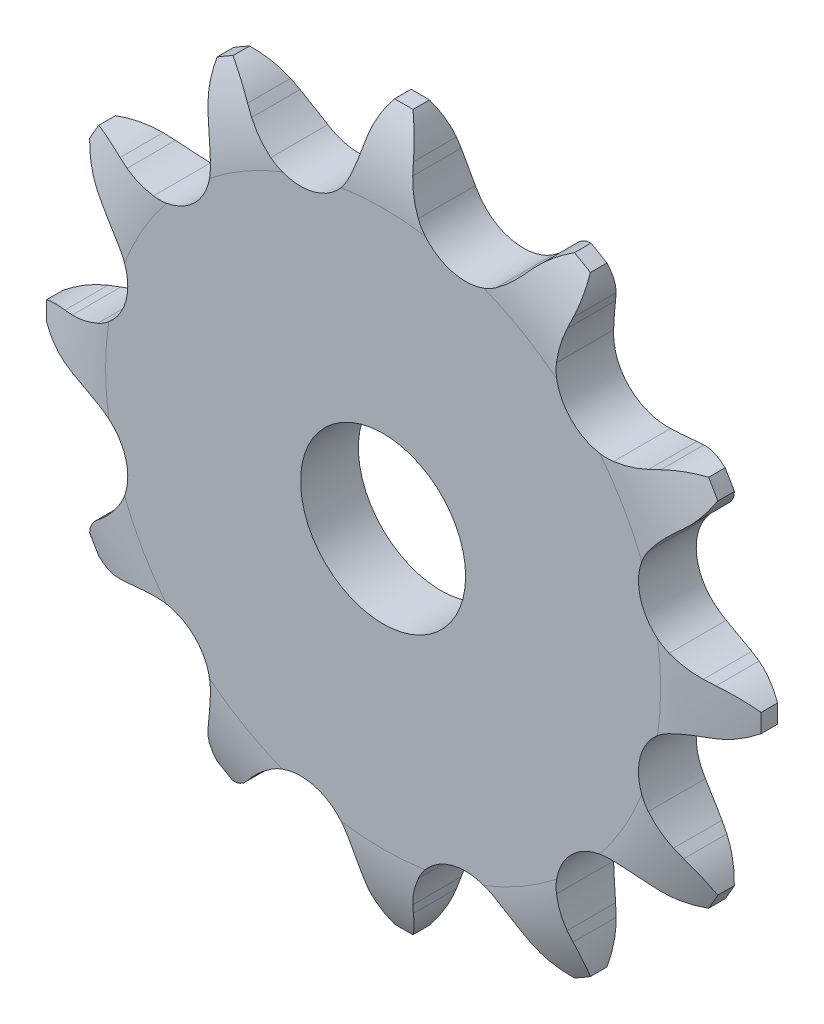
SolidWorks part; units mm, degrees
ref_plane "Front Plane" through (0, 0, 0) normal (0, 0, 1) x (1, 0, 0)
ref_plane "Top Plane" through (0, 0, 0) normal (0, 1, 0) x (1, 0, 0)
ref_plane "Right Plane" through (0, 0, 0) normal (1, 0, 0) x (0, 0, -1)
sketch "Sketch0" plane through (0, 0, 0) normal (0, 0, 1) x (1, 0, 0)
  line L0 (4, -14.9282) -> (0, 0) construction
  line L1 (0, 0) -> (10.9282, -10.9282) construction
  line L2 (0, 0) -> (-4, -14.9282) construction
  line L3 (4, -14.9282) -> (10.9282, -10.9282) construction
  line L4 (4, -14.9282) -> (-4, -14.9282) construction
  line L5 (6.9269, -14.2183) -> (6.5992, -13.85)
  line L6 (4, -14.9282) -> (0, -16) construction
  line L7 (1.1103, -15.7769) -> (1.21, -15.294)
  line L8 (0, -14.9282) -> (0, -17.3282) construction
  line L9 (5.463, -12.8389) -> (1.7057, -18.2048) construction
  line L10 (0, 0) -> (0, -14.9282) construction
  line L11 (6.5992, -13.85) -> (1.7057, -18.2048) construction
  line L12 (0, -17.3282) -> (0, -17.8633) construction
  line L13 (10.0622, -11.4282) -> (6.9269, -14.2183) construction
  circle A0 centre (0, 0) radius 17.3282 construction
  circle A1 centre (0, 0) radius 15.4548 construction
  arc A2 (-3.8269, -19.0429) -> (12.8356, -14.5782) centre (0, 0) ccw
  circle A3 centre (0, 0) radius 17.8633 construction
  circle A4 centre (4, -14.9282) radius 2.5 construction
  arc A7 (5.463, -12.8389) -> (1.6884, -13.8503) centre (4, -14.9282) ccw
  circle A8 centre (4, -14.9282) radius 2.5506 construction
  arc A9 (6.9269, -14.2183) -> (12.8356, -14.5782) centre (10.0622, -11.4282) ccw
  arc A10 (6.5992, -13.85) -> (5.463, -12.8389) centre (1.7057, -18.2048) ccw
  arc A11 (1.1103, -15.7769) -> (-3.8269, -19.0429) centre (-3, -14.9282) cw
  arc A12 (1.21, -15.294) -> (1.6884, -13.8503) centre (7.6252, -16.6187) cw
  dimension "D1" = 2.5506
  dimension "R" = 2.5506
sketch "Sketch1" plane through (0, 0, 0) normal (1, 0, 0) x (0, 0, -1)
  line L0 (1.4, 0) -> (-1.4, 0)
  line L1 (-1.4, 0) -> (-1.4, 13.4552)
  line L2 (-1.4, 15.4548) -> (0, 15.4548) construction
  line L3 (-0.4, 17.3282) -> (0.4, 17.3282)
  line L5 (1.4, 13.4552) -> (1.4, 0)
  line L7 (0, 17.3282) -> (0, 0) construction
  line L8 (-1.4, 13.4552) -> (1.4, 13.4552) construction
  line L9 (0, 17.3282) -> (0, -17.3282) construction
  line L10 (-1.4, 13.4552) -> (-1.4, 17.3282) construction
  line L11 (-1.4, 17.3282) -> (-0.4, 17.3282) construction
  line L12 (0.4, 17.3282) -> (1.4, 17.3282) construction
  line L13 (1.4, 17.3282) -> (1.4, 13.4552) construction
  line L14 (0, 0) -> (-6.4008, 0) construction
  line L15 (-1.4, 15.4548) -> (-1.4, 10.1548) construction
  line L22 (1.4, 0) -> (-11.6, 0) construction
  line L24 (-1.4, 0) -> (-1.4, 10.1548) construction
  arc A0 (-0.4, 17.3282) -> (-1.4, 13.4552) centre (6.6, 13.4552) ccw
  arc A1 (0.4, 17.3282) -> (1.4, 13.4552) centre (-6.6, 13.4552) cw
  dimension "R" = 8
revolve "Revolve1" add sketch "Sketch1" angle 360 mid plane about L0
extrude "Cut-Extrude1" cut sketch "Sketch0" against normal through all and the other way through all
pattern_circular "CirPattern1" count 12 over 360 about axis through (0, 0, 0) along (0, 0, 1) of "Cut-Extrude1"
sketch "Sketch2" plane through (0, 0, 0) normal (0, 0, 1) x (1, 0, 0)
  circle A0 centre (0, 0) radius 4 construction
  circle A1 centre (0, 0) radius 10
  circle A2 centre (0, 0) radius 17.33 construction
  dimension "Bore" = 8
  dimension "Hub Dia." = 20
  dimension "OD" = 34.66
extrude "Boss-Extrude1" add sketch "Sketch2" along normal up to vertex (11.6 mm away) from surface at 1.4 starting at face at (0, 0, 1.4)
sketch "Sketch3" plane through (0, 0, 0) normal (0, 0, 1) x (1, 0, 0)
  circle A0 centre (0, 0) radius 4 construction
  circle A1 centre (0, 0) radius 4
extrude "Cut-Extrude2" cut sketch "Sketch3" along normal through all and the other way through all
sketch "Sketch4" plane through (0, 0, 0) normal (1, 0, 0) x (0, 0, -1)
  line L0 (-11.6, 10) -> (-11.6, 9.5)
  line L1 (-1.4, 17.3282) -> (-3.5, 17.3282)
  line L2 (-1.4, 17.3282) -> (-1.4, 10.1548)
  line L3 (-1.4, 10.1548) -> (-3.5, 10.1548)
  line L4 (-3.5, 17.3282) -> (-3.5, 10.1548)
  line L9 (-11.6, 9.5) -> (-11.1, 10)
  line L10 (-11.1, 10) -> (-11.6, 10)
  dimension "C" = 0.5
  dimension "D3" = 2.1
revolve "Cut-Revolve1" cut sketch "Sketch4" angle 360 mid plane about L22
sketch "Sketch5" plane through (0, 0, 0) normal (0, 0, 1) x (1, 0, 0)
  circle A0 centre (0, 0) radius 17.33 construction
  circle A1 centre (0, 0) radius 17.33
extrude "Cut-Extrude3" [suppressed] cut sketch "Sketch5" against normal through all and the other way through all flip side to cut
sketch "Sketch6" plane through (0, 0, 1.4) normal (0, 0, 1) x (1, 0, 0)
  circle A0 centre (0, 0) radius 10
  dimension "D1" = 20
extrude "Cut-Extrude4" cut sketch "Sketch6" along normal blind 20
equation "\"360/N@Sketch0\" = 360/\"Teeth@CirPattern1\""
equation "\"Ds@Sketch0\" = 1.005 * \"Dr@Sketch0\" + ( 0.003 * 25.4 ) "
equation "\"R@Sketch0\" = 1/2 * \"Ds@Sketch0\""
equation "\"A@Sketch0\" = 35 +  ( 60 / \"Teeth@CirPattern1\" ) "
equation "\"B@Sketch0\" = 18 -  ( 56 / \"Teeth@CirPattern1\" )"
equation "\"ac@Sketch0\" = 0.8 * \"Dr@Sketch0\""
equation "\"ab@Sketch0\" = 1.4 * \"Dr@Sketch0\""
equation "\"J@Sketch0\" = 0.3 * \"Pitch@Sketch0\""
equation "\"D3@Sketch4\" = \"t@Sketch1\" * 3 / 4"
